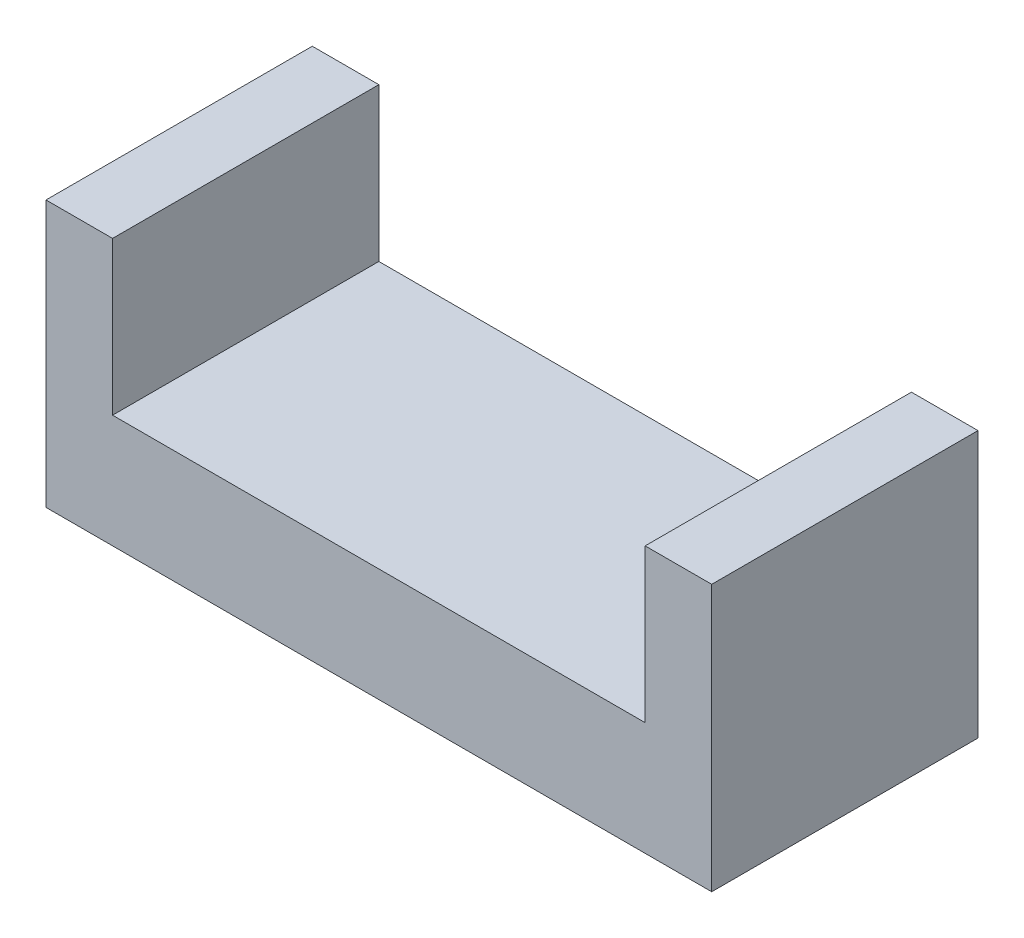
SolidWorks part; units mm, degrees
ref_plane "前基準面" through (0, 0, 0) normal (0, 0, 1) x (1, 0, 0)
ref_plane "上基準面" through (0, 0, 0) normal (0, 1, 0) x (1, 0, 0)
ref_plane "右基準面" through (0, 0, 0) normal (1, 0, 0) x (0, 0, -1)
sketch "草圖1" plane through (0, 0, 0) normal (0, 0, 1) x (1, 0, 0)
  line L1 (-25, 10) -> (25, 10)
  line L2 (-25, 10) -> (-25, -10)
  line L3 (-25, -10) -> (25, -10)
  line L4 (25, 10) -> (25, -10)
  line L5 (-25, 10) -> (25, -10) construction
  line L6 (-25, -10) -> (25, 10) construction
  line L7 (-20, 10) -> (20, 10)
  line L8 (-20, 10) -> (-20, -1.5)
  line L9 (-20, -1.5) -> (20, -1.5)
  line L10 (20, 10) -> (20, -1.5)
  point P0 (0, 0)
  point P10 (0, -1.5)
  point P11 (0, 10)
  dimension "D1" = 50
  dimension "D2" = 20
  dimension "D3" = 40
  dimension "D4" = 8.5
extrude "填料-伸長1" add sketch "草圖1" along normal blind 20 contours L1 L10 L9 L8 L2 L3 L4
